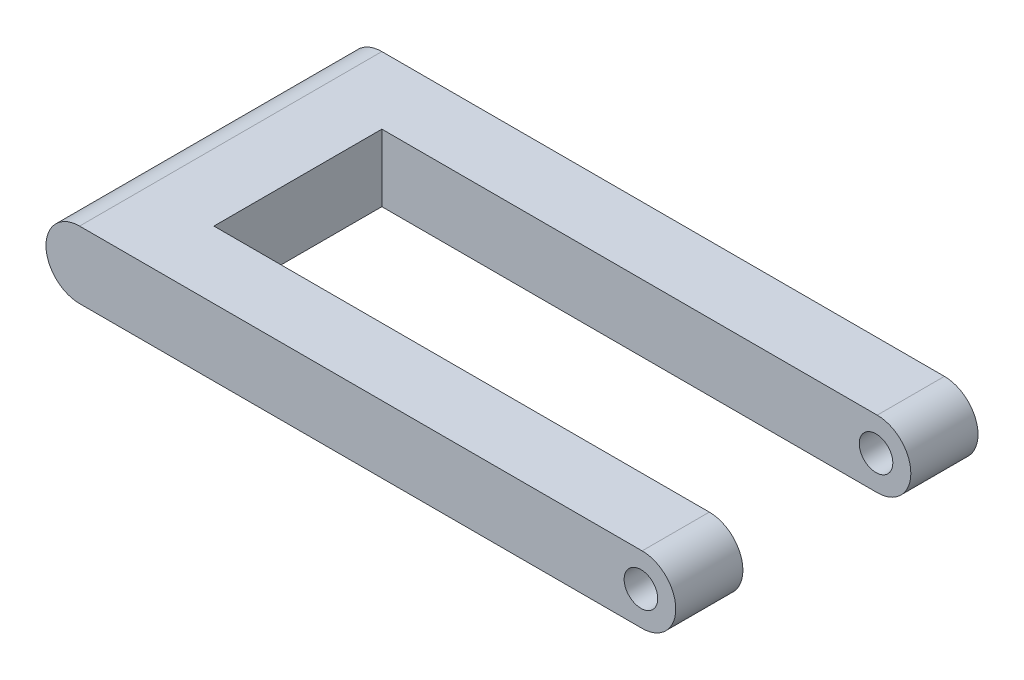
SolidWorks part; units mm, degrees
ref_plane "Front Plane" through (0, 0, 0) normal (0, 0, 1) x (1, 0, 0)
ref_plane "Top Plane" through (0, 0, 0) normal (0, 1, 0) x (1, 0, 0)
ref_plane "Right Plane" through (0, 0, 0) normal (1, 0, 0) x (0, 0, -1)
sketch "Sketch1" plane through (0, 0, 0) normal (0, 0, 1) x (1, 0, 0)
  line L1 (0, 0) -> (33.5, 0)
  line L3 (0, 4) -> (33.5, 4)
  arc A0 (33.5, 4) -> (33.5, 0) centre (33.5, 2) cw
  arc A1 (0, 4) -> (0, 0) centre (0, 2) ccw
  dimension "D1" = 33.5
  dimension "D2" = 4
extrude "Boss-Extrude1" add sketch "Sketch1" along normal blind 4
sketch "Sketch2" plane through (0, 0, 4) normal (0, 0, 1) x (1, 0, 0)
  line L0 (0, 0) -> (33.5, 0) construction
  line L1 (4, 0) -> (0, 0)
  line L2 (4, 0) -> (4, 4)
  line L3 (4, 4) -> (0, 4)
  arc A0 (0, 4) -> (0, 0) centre (0, 2) ccw
  dimension "D1" = 4
extrude "Boss-Extrude2" add sketch "Sketch2" along normal blind 10
ref_plane "Plane1" through (0, 0, 14) normal (0, 0, 1) x (1, 0, 0)
sketch "Sketch3" plane through (0, 0, 14) normal (0, 0, 1) x (1, 0, 0)
  line L0 (0, 4) -> (33.5, 4)
  line L2 (33.5, 0) -> (0, 0)
  arc A0 (0, 4) -> (0, 0) centre (0, 2) ccw
  arc A1 (33.5, 4) -> (33.5, 0) centre (33.5, 2) cw
extrude "Boss-Extrude3" add sketch "Sketch3" along normal blind 4
sketch "Sketch4" plane through (0, 0, 18) normal (0, 0, 1) x (1, 0, 0)
  line L0 (33.5, 4) -> (0, 4) construction
  circle A0 centre (33.4273, 2) radius 1
  dimension "D1" = 2
  dimension "D2" = 2
extrude "Cut-Extrude4" cut sketch "Sketch4" against normal blind 26
